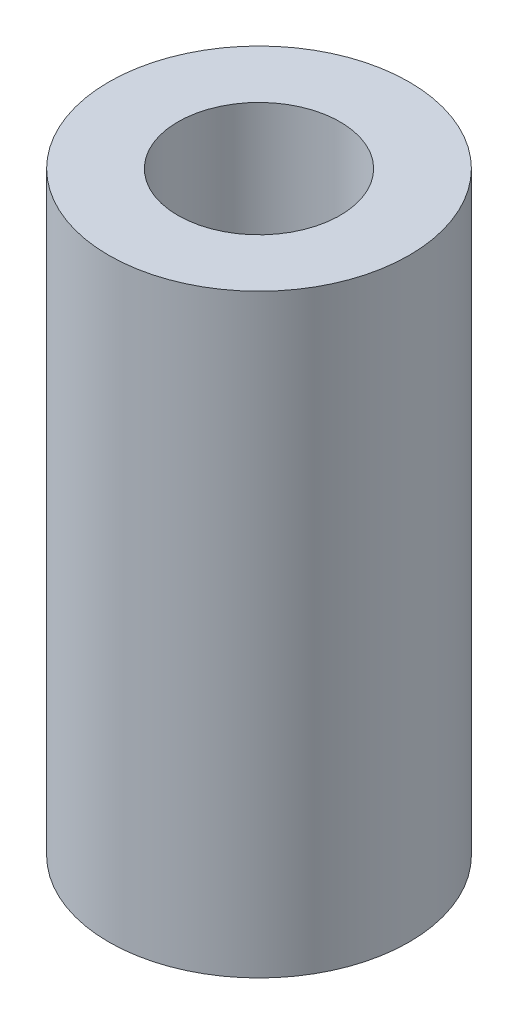
SolidWorks part; units mm, degrees
ref_plane "Front Plane" through (0, 0, 0) normal (0, 0, 1) x (1, 0, 0)
ref_plane "Top Plane" through (0, 0, 0) normal (0, 1, 0) x (1, 0, 0)
ref_plane "Right Plane" through (0, 0, 0) normal (1, 0, 0) x (0, 0, -1)
sketch "Sketch1" plane through (0, 0, 0) normal (0, 1, 0) x (1, 0, 0)
  circle A0 centre (0, 0) radius 3.429
  circle A1 centre (0, 0) radius 6.35
  dimension "D1" = 6.858
  dimension "D2" = 12.7
extrude "Boss-Extrude1" add sketch "Sketch1" along normal blind 25.146
equation "\"tightTol\" = 0.005in"
equation "\"normTol\"= 0.01in"
equation "\"looseTol\"= 0.02in"
equation "\"D1@Sketch1\"=\"looseTol\"+0.25"
equation "\"D1@Boss-Extrude1\"=1.00in-\"normTol\""
